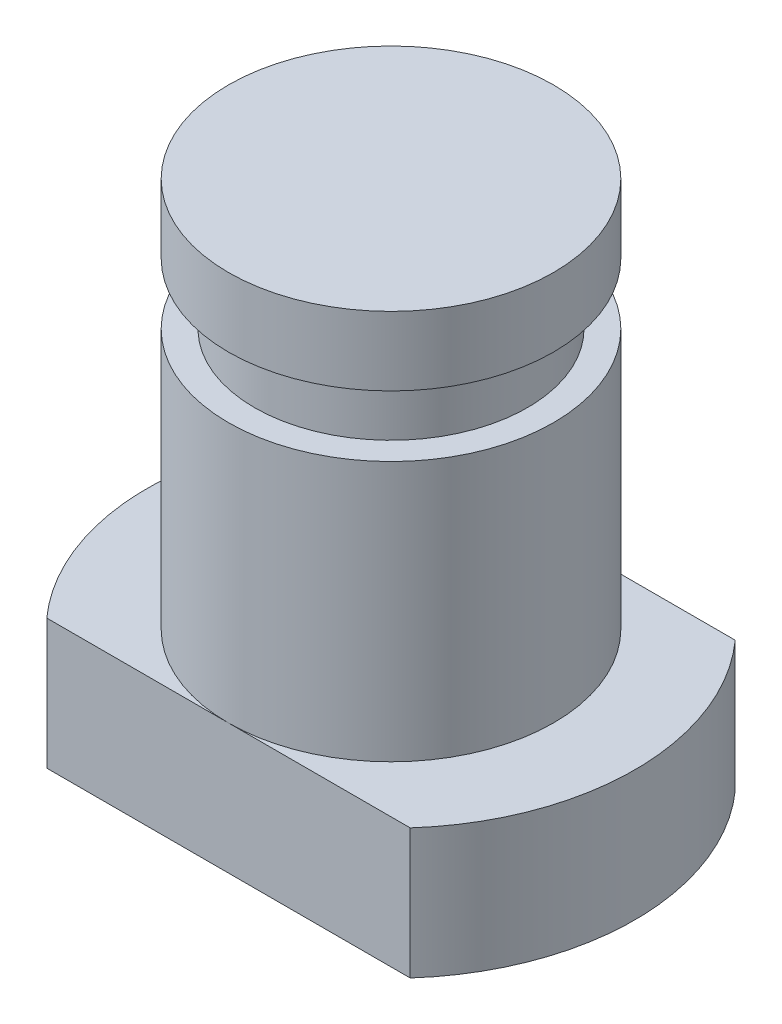
SolidWorks part; units mm, degrees
material "AISI 1015 Steel, Cold Drawn (SS)"
ref_plane "Front Plane" through (0, 0, 0) normal (0, 0, 1) x (1, 0, 0)
ref_plane "Top Plane" through (0, 0, 0) normal (0, 1, 0) x (1, 0, 0)
ref_plane "Right Plane" through (0, 0, 0) normal (1, 0, 0) x (0, 0, -1)
sketch "Sketch1" plane through (0, 0, 0) normal (0, 1, 0) x (1, 0, 0)
  circle A0 centre (0, 0) radius 3.175
  dimension "D1" = 6.35
extrude "Boss-Extrude1" add sketch "Sketch1" along normal blind 7.62
sketch "Sketch2" plane through (0, 0, 0) normal (0, -1, 0) x (1, 0, 0)
  line L0 (-10.6761, 0) -> (14.4716, 0) construction
  line L1 (-3.5498, 3.175) -> (3.5498, 3.175)
  line L2 (-3.5498, -3.175) -> (3.5498, -3.175)
  circle A2 centre (0, 0) radius 3.175 construction
  arc A3 (-3.5498, 3.175) -> (-3.5498, -3.175) centre (0, 0) ccw
  arc A4 (3.5498, -3.175) -> (3.5498, 3.175) centre (0, 0) ccw
  dimension "D1" = 9.525
extrude "Boss-Extrude2" add sketch "Sketch2" along normal blind 2.54
ref_plane "Plane1" through (0, 5.08, 0) normal (0, 1, 0) x (1, 0, 0)
sketch "Sketch6" plane through (0, 5.08, 0) normal (0, 1, 0) x (1, 0, 0)
  circle A0 centre (0, 0) radius 2.667
  dimension "D1" = 5.334
extrude "Cut-Extrude1" cut sketch "Sketch6" along normal blind 1.1938 flip side to cut
equation "\"0.3n\"=0.4"
